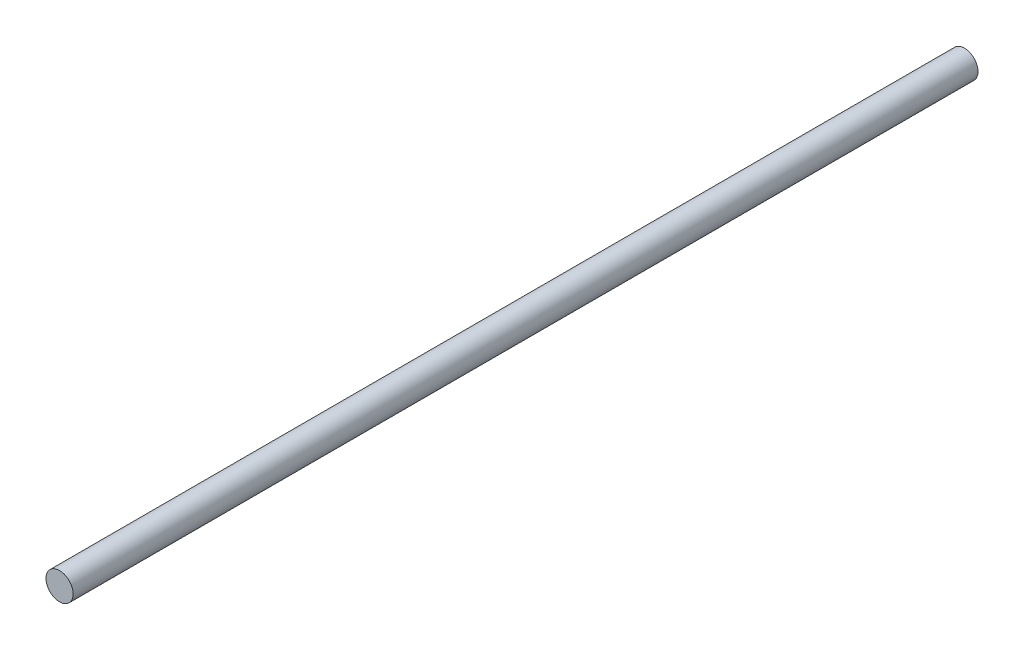
SolidWorks part; units mm, degrees
ref_plane "Alzado" through (0, 0, 0) normal (0, 0, 1) x (1, 0, 0)
ref_plane "Planta" through (0, 0, 0) normal (0, 1, 0) x (1, 0, 0)
ref_plane "Vista lateral" through (0, 0, 0) normal (1, 0, 0) x (0, 0, -1)
sketch "Croquis1" plane through (0, 0, 0) normal (0, 0, 1) x (1, 0, 0)
  circle A0 centre (0, 0) radius 3
  dimension "D1" = 6
extrude "Saliente-Extruir1" add sketch "Croquis1" along normal blind 200
